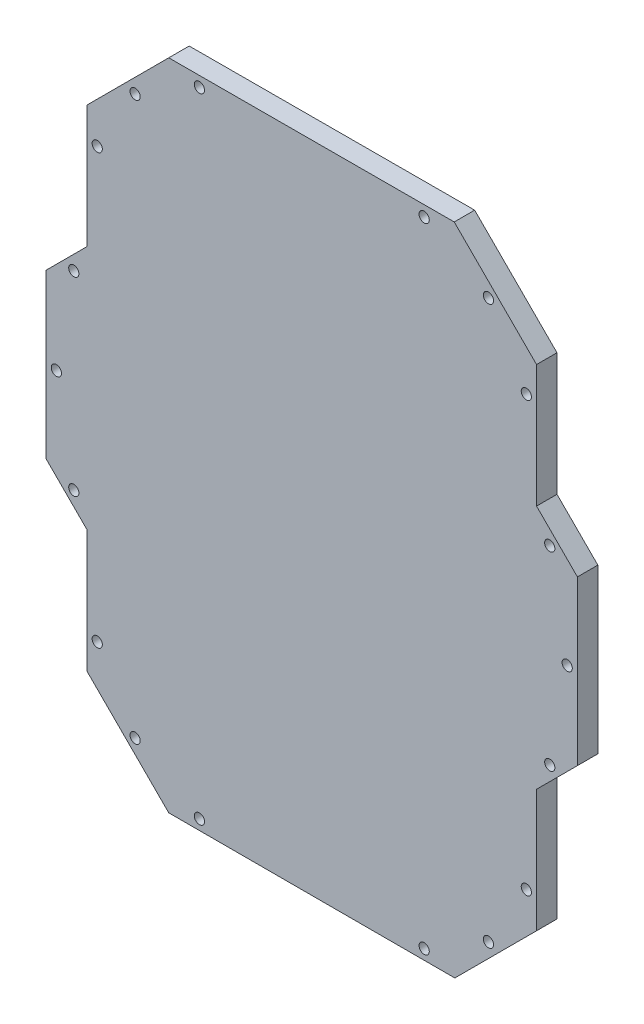
SolidWorks part; units mm, degrees
ref_plane "Front Plane" through (0, 0, 0) normal (0, 0, 1) x (1, 0, 0)
ref_plane "Top Plane" through (0, 0, 0) normal (0, 1, 0) x (1, 0, 0)
ref_plane "Right Plane" through (0, 0, 0) normal (1, 0, 0) x (0, 0, -1)
sketch "Model" plane through (0, 0, 0) normal (0, 0, 1) x (1, 0, 0)
  line L0 (105.0551, 3.7198) -> (125.0551, 23.7198)
  line L1 (104.9098, 163.865) -> (125.0551, 143.7198)
  line L2 (35.0551, 3.7198) -> (15.0551, 23.7198)
  line L3 (5.0551, 63.7198) -> (5.0551, 103.7198)
  line L4 (35.0588, 163.7235) -> (15.0551, 143.7198)
  line L5 (15.0551, 23.7198) -> (15.0551, 53.7198)
  line L6 (5.0551, 63.7198) -> (15.0551, 53.7198)
  line L7 (15.0551, 143.7198) -> (15.0551, 113.7198)
  line L8 (5.0551, 103.7198) -> (15.0551, 113.7198)
  line L9 (135.0551, 63.7198) -> (135.0551, 103.7198)
  line L10 (125.0551, 23.7198) -> (125.0551, 53.7198)
  line L11 (135.0551, 63.7198) -> (125.0551, 53.7198)
  line L12 (125.0551, 143.7198) -> (125.0551, 113.7198)
  line L13 (135.0551, 103.7198) -> (125.0551, 113.7198)
  line L14 (35.0551, 3.7198) -> (105.0551, 3.7198)
  line L15 (35.0588, 163.7235) -> (104.9098, 163.865)
  circle A0 centre (97.5551, 6.2198) radius 1.25
  circle A1 centre (122.5551, 31.2198) radius 1.25
  circle A2 centre (113.2873, 15.4875) radius 1.25
  circle A3 centre (42.5551, 6.2198) radius 1.25
  circle A4 centre (17.5551, 31.2198) radius 1.25
  circle A5 centre (26.8228, 15.4875) radius 1.25
  circle A6 centre (97.5551, 161.2198) radius 1.25
  circle A7 centre (122.5551, 136.2198) radius 1.25
  circle A8 centre (113.2873, 151.952) radius 1.25
  circle A9 centre (42.5551, 161.2198) radius 1.25
  circle A10 centre (17.5551, 136.2198) radius 1.25
  circle A11 centre (26.8228, 151.952) radius 1.25
  circle A12 centre (11.8228, 60.4875) radius 1.25
  circle A13 centre (7.5551, 83.7198) radius 1.25
  circle A14 centre (11.8228, 106.952) radius 1.25
  circle A15 centre (128.2873, 60.4875) radius 1.25
  circle A16 centre (132.5551, 83.7198) radius 1.25
  circle A17 centre (128.2873, 106.952) radius 1.25
extrude "Boss-Extrude1" add sketch "Model" along normal blind 5
